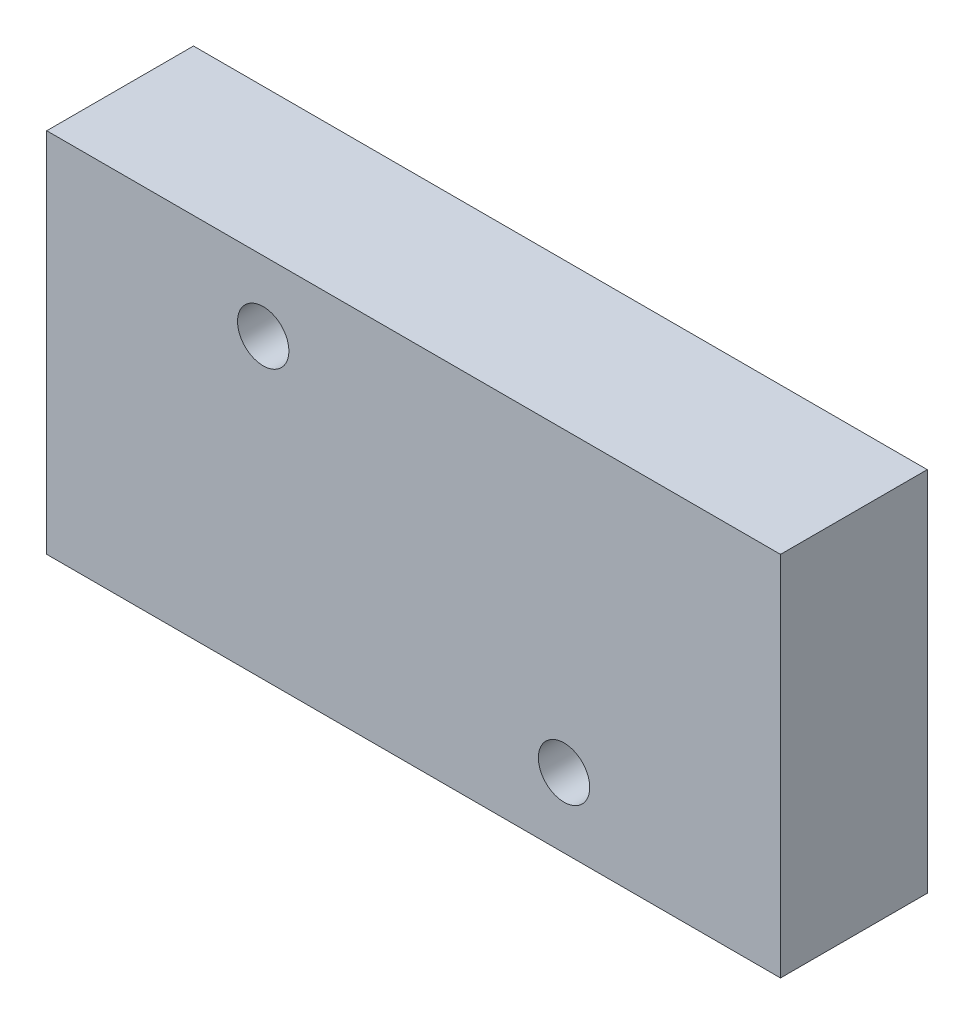
SolidWorks part; units mm, degrees
ref_plane "Front Plane" through (0, 0, 0) normal (0, 0, 1) x (1, 0, 0)
ref_plane "Top Plane" through (0, 0, 0) normal (0, 1, 0) x (1, 0, 0)
ref_plane "Right Plane" through (0, 0, 0) normal (1, 0, 0) x (0, 0, -1)
sketch "Sketch1" plane through (0, 0, 0) normal (0, 0, 1) x (1, 0, 0)
  line L1 (-31.6279, 18.314) -> (18.3721, 18.314)
  line L2 (-31.6279, 18.314) -> (-31.6279, -6.686)
  line L3 (-31.6279, -6.686) -> (18.3721, -6.686)
  line L4 (18.3721, 18.314) -> (18.3721, -6.686)
  point P4 (18.3721, 5.814)
  dimension "D1" = 50
  dimension "D2" = 25
extrude "Boss-Extrude1" add sketch "Sketch1" along normal blind 10
sketch "Sketch2" plane through (0, 0, 10) normal (0, 0, 1) x (1, 0, 0)
  line L0 (18.3721, 18.314) -> (-31.6279, 18.314) construction
  line L1 (-31.6279, 18.314) -> (-31.6279, -6.686) construction
  circle A0 centre (-16.8779, 13.564) radius 1.75
  dimension "D1" = 3.5
  dimension "D2" = 4.75
  dimension "D3" = 14.75
extrude "Cut-Extrude1" cut sketch "Sketch2" against normal blind 10
sketch "Sketch3" plane through (0, 0, 10) normal (0, 0, 1) x (1, 0, 0)
  line L0 (-31.6279, -6.686) -> (18.3721, -6.686) construction
  line L1 (18.3721, -6.686) -> (18.3721, 18.314) construction
  circle A0 centre (3.6221, -1.936) radius 1.75
  dimension "D1" = 3.5
  dimension "D2" = 4.75
  dimension "D3" = 14.75
extrude "Cut-Extrude2" cut sketch "Sketch3" against normal blind 10
